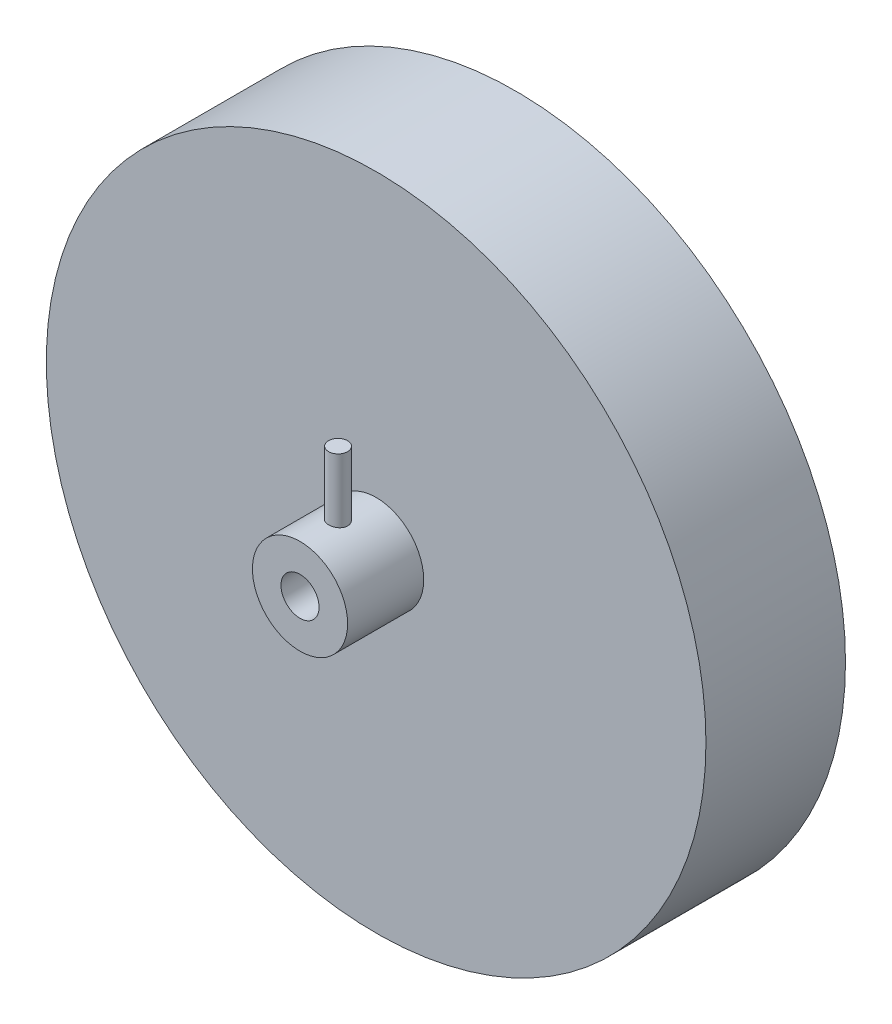
SolidWorks part; units mm, degrees
ref_plane "Front Plane" through (0, 0, 0) normal (0, 0, 1) x (1, 0, 0)
ref_plane "Top Plane" through (0, 0, 0) normal (0, 1, 0) x (1, 0, 0)
ref_plane "Right Plane" through (0, 0, 0) normal (1, 0, 0) x (0, 0, -1)
sketch "Sketch1" plane through (0, 0, 0) normal (0, 0, 1) x (1, 0, 0)
  circle A0 centre (0, 0) radius 52
  dimension "D1" = 104
extrude "Boss-Extrude1" add sketch "Sketch1" along normal mid plane 22
sketch "Sketch2" plane through (0, 0, 11) normal (0, 0, 1) x (1, 0, 0)
  circle A0 centre (0, 0) radius 7.5
  dimension "D1" = 15
extrude "Boss-Extrude2" add sketch "Sketch2" along normal blind 12
sketch "Sketch3" plane through (0, 0, 0) normal (0, 1, 0) x (1, 0, 0)
  line L0 (0, 11) -> (0, -23) construction
  line L2 (52, 11) -> (-52, 11) construction
  line L3 (-7.5, -23) -> (7.5, -23) construction
  circle A0 centre (0, -17) radius 1.5
  dimension "D1" = 3
  dimension "D2" = 6
extrude "Boss-Extrude3" add sketch "Sketch3" along normal blind 17.5
sketch "Sketch4" plane through (0, 0, 23) normal (0, 0, -1) x (-1, 0, 0)
  circle A0 centre (0, 0) radius 3
  dimension "D1" = 6
extrude "Cut-Extrude3" cut sketch "Sketch4" along normal blind 12
